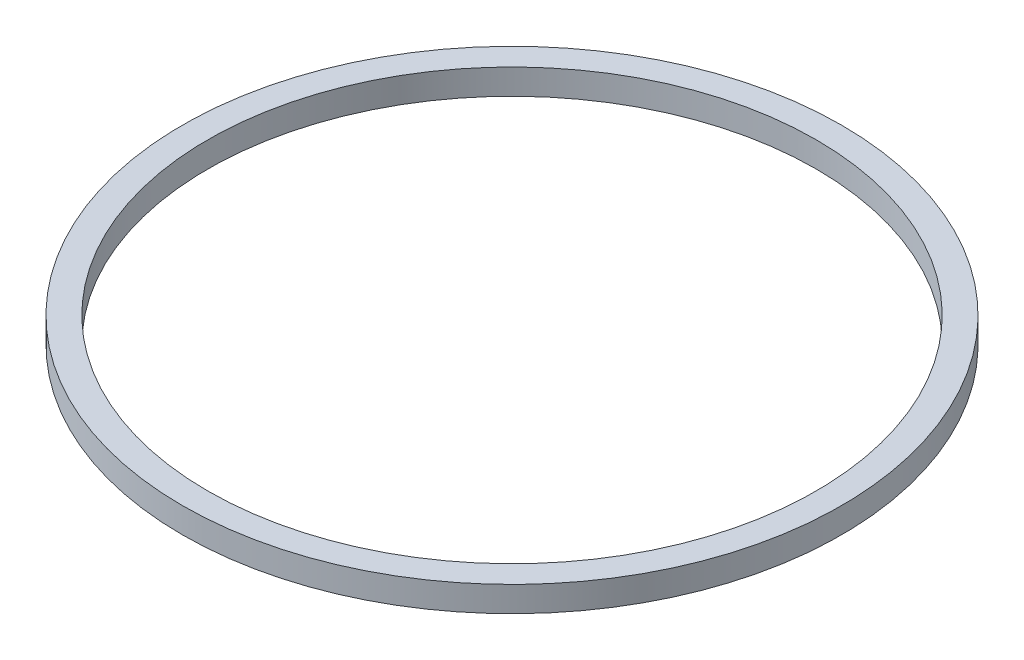
SolidWorks part; units mm, degrees
ref_plane "Ön Düzlem" through (0, 0, 0) normal (0, 0, 1) x (1, 0, 0)
ref_plane "Üst Düzlem" through (0, 0, 0) normal (0, 1, 0) x (1, 0, 0)
ref_plane "Sağ Düzlem" through (0, 0, 0) normal (1, 0, 0) x (0, 0, -1)
sketch "Çizim1" plane through (0, 0, 0) normal (0, 1, 0) x (1, 0, 0)
  circle A0 centre (0, 0) radius 130
  circle A1 centre (0, 0) radius 120
extrude "Yükseklik-Ekstrüzyon1" add sketch "Çizim1" along normal blind 10
